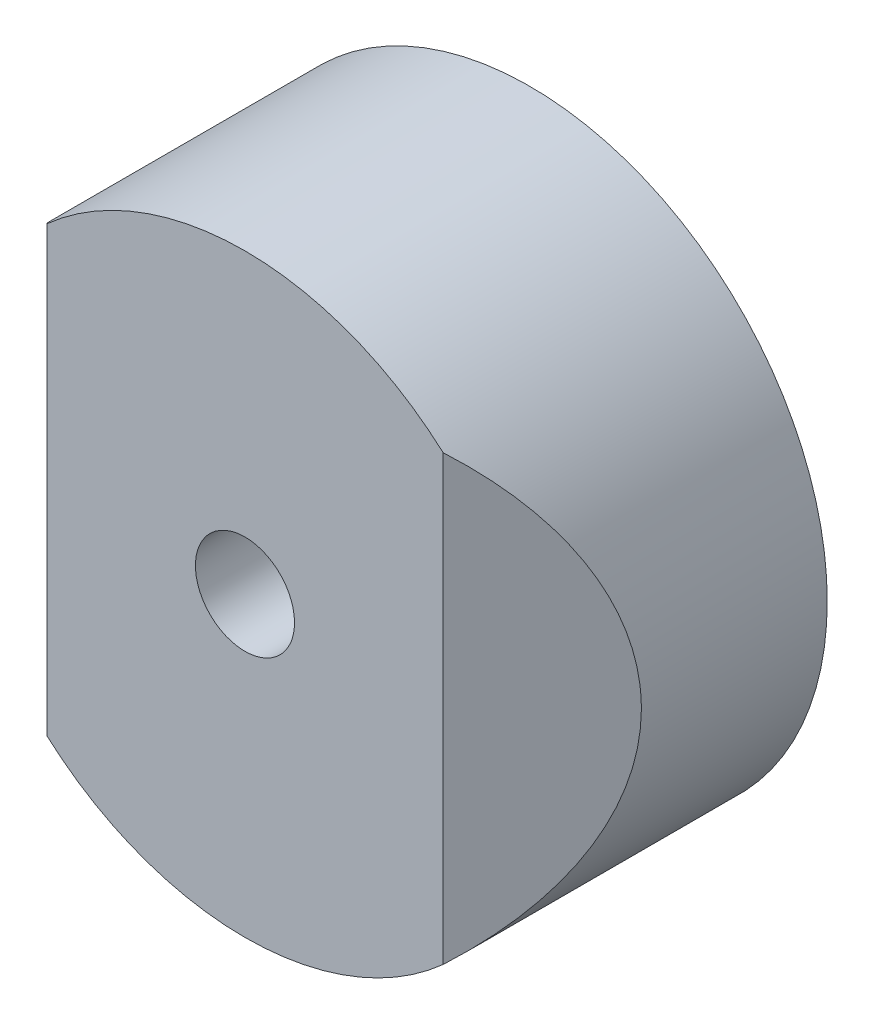
SolidWorks part; units mm, degrees
material "Ceramic Insulation"
ref_plane "Front Plane" through (0, 0, 0) normal (0, 0, 1) x (1, 0, 0)
ref_plane "Top Plane" through (0, 0, 0) normal (0, 1, 0) x (1, 0, 0)
ref_plane "Right Plane" through (0, 0, 0) normal (1, 0, 0) x (0, 0, -1)
sketch "Sketch1" plane through (0, 0, 0) normal (0, 0, 1) x (1, 0, 0)
  circle A0 centre (0, 0) radius 6.35
  circle A1 centre (0, 0) radius 38.1
  dimension "D2" = 12.7
  dimension "D1" = 31.75
extrude "Boss-Extrude1" add sketch "Sketch1" against normal blind 36.5125
sketch "Sketch2" plane through (0, 0, 0) normal (0, 1, 0) x (1, 0, 0)
  line L0 (-38.1, 12.7) -> (-25.4, 0)
  line L1 (-38.1, 36.5125) -> (-38.1, 0) construction
  line L2 (-38.1, 0) -> (38.1, 0) construction
  line L3 (0, 36.5125) -> (0, 0) construction
  line L4 (6.35, 36.5125) -> (-6.35, 36.5125) construction
  line L5 (-38.1, 12.7) -> (-38.1, 0)
  line L6 (-38.1, 0) -> (-25.4, 0)
  line L7 (38.1, 0) -> (25.4, 0)
  line L8 (38.1, 12.7) -> (38.1, 0)
  line L9 (38.1, 12.7) -> (25.4, 0)
  dimension "D1" = 12.7
  dimension "D2" = 45
extrude "Cut-Extrude1" cut sketch "Sketch2" against normal through all both and the other way through all
equation "\"ID\"= .5"
equation "\"D2@Sketch1\"=\"ID\""
equation "\"L\"= 1.5"
equation "\"D1@Boss-Extrude1\"=\"L\"-1/16"
equation "\"InsulationThickness\"= 1.25"
equation "\"D1@Sketch1\"=\"InsulationThickness\""
